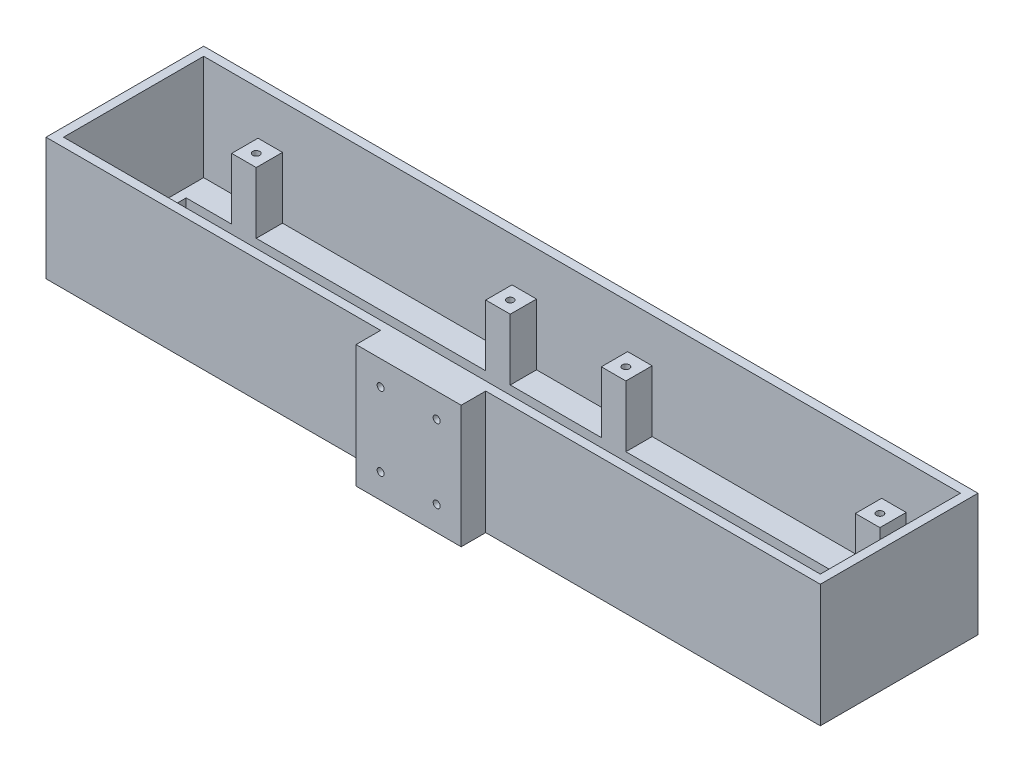
SolidWorks part; units mm, degrees
ref_plane "Front Plane" through (0, 0, 0) normal (0, 0, 1) x (1, 0, 0)
ref_plane "Top Plane" through (0, 0, 0) normal (0, 1, 0) x (1, 0, 0)
ref_plane "Right Plane" through (0, 0, 0) normal (1, 0, 0) x (0, 0, -1)
sketch "Sketch1" plane through (0, 0, 0) normal (0, 1, 0) x (1, 0, 0)
  line L0 (0, 0) -> (0, 46.1847) construction
  line L1 (-110.5, 22.5) -> (110.5, 22.5)
  line L2 (-110.5, 22.5) -> (-110.5, -22.5)
  line L3 (-110.5, -22.5) -> (110.5, -22.5)
  line L4 (110.5, 22.5) -> (110.5, -22.5)
  line L5 (0, 46.1847) -> (0, 0) construction
  line L6 (0, 0) -> (-132.7699, 0) construction
  line L8 (-27.2143, -70.7906) -> (-28.1151, -66.2212) construction
  dimension "D1" = 45
  dimension "D2" = 221
  dimension "D3" = 110.5
  dimension "D4" = 22.5
extrude "Boss-Extrude1" add sketch "Sketch1" along normal blind 5
sketch "Sketch2" plane through (0, 5, 0) normal (0, 1, 0) x (1, 0, 0)
  line L0 (0, 0) -> (0, 63.4853) construction
  line L1 (-105.5, 12.5) -> (105.5, 12.5)
  line L2 (-105.5, 12.5) -> (-105.5, -12.5)
  line L3 (-105.5, -12.5) -> (105.5, -12.5)
  line L4 (105.5, 12.5) -> (105.5, -12.5)
  line L5 (0, 63.4853) -> (0, -74.9421) construction
  line L6 (0, -74.9421) -> (0, 0) construction
  line L7 (0, 0) -> (-181.4639, 0) construction
  line L8 (-181.4639, 0) -> (180.3828, 0) construction
  point P8 (0, -5.7284)
  dimension "D1" = 25
  dimension "D2" = 211
  dimension "D3" = 105.5
  dimension "D4" = 12.5
extrude "Cut-Extrude1" cut sketch "Sketch2" against normal blind 2.5
sketch "Sketch3" plane through (0, 2.5, 0) normal (0, 1, 0) x (1, 0, 0)
  line L0 (0, -84.5319) -> (0, 82.5317) construction
  line L1 (0, 82.5317) -> (0, 0) construction
  line L2 (0, 0) -> (-169.1228, 0) construction
  line L3 (-169.1228, 0) -> (142.1549, 0) construction
  circle A0 centre (-53, 0) radius 8
  circle A1 centre (53, 0) radius 8
  dimension "D1" = 53
  dimension "D2" = 53
extrude "Cut-Extrude2" cut sketch "Sketch3" against normal blind 2.5
sketch "Sketch4" plane through (0, 5, 0) normal (0, 1, 0) x (1, 0, 0)
  line L0 (0, 66.7486) -> (0, -72.9211) construction
  line L1 (0, -72.9211) -> (0, 0) construction
  line L2 (0, 0) -> (-130.6196, 0) construction
  line L3 (-130.6196, 0) -> (143.6753, 0) construction
sketch "Sketch6" plane through (0, 5, 0) normal (0, 1, 0) x (1, 0, 0)
  line L1 (-110.5, -22.5) -> (110.5, -22.5)
  line L3 (110.5, 22.5) -> (-110.5, 22.5)
  line L6 (-110.5, -20) -> (110.5, -20)
  line L10 (0, 66.7486) -> (0, -72.9211) construction
  line L11 (-110.5, -20) -> (-110.5, -22.5)
  line L12 (110.5, -20) -> (110.5, -22.5)
  line L13 (-110.5, 22.5) -> (-110.5, 20)
  line L14 (-110.5, 22.5) -> (-110.5, -22.5) construction
  line L15 (-110.5, 20) -> (110.5, 20)
  line L16 (110.5, -22.5) -> (110.5, 22.5) construction
  line L17 (110.5, 20) -> (110.5, 22.5)
  line L19 (108, 20) -> (110.5, 20)
  line L20 (108, 20) -> (108, -20)
  line L25 (108, -20) -> (110.5, -20)
  line L26 (110.5, 20) -> (110.5, -20)
  line L31 (-110.5, 20) -> (-108, 20)
  line L32 (-110.5, 20) -> (-110.5, -20)
  line L33 (-110.5, -20) -> (-108, -20)
  line L34 (-108, 20) -> (-108, -20)
  line M12 (-110.5, 22.5) -> (-110.5, -22.5)
  line M14 (110.5, -22.5) -> (110.5, 22.5)
  line M15 (110.5, 22.5) -> (-110.5, 22.5)
  dimension "D2" = 2.5
  dimension "D3" = 2.5
  dimension "D4" = 2.5
  dimension "D6" = 2.5
  dimension "D7" = 40
  dimension "D8" = 108
  dimension "D9" = 221
  dimension "D10" = 2.5
extrude "Boss-Extrude3" add sketch "Sketch6" along normal blind 30 contours L34 L15 L6 M12 | L15 M12 M14 M15 | L20 L25 L26 L19
sketch "Sketch7" plane through (0, 5, 0) normal (0, 1, 0) x (1, 0, 0)
  line L0 (105.5, 12.5) -> (-105.5, 12.5) construction
  line L1 (-92.5, 20) -> (-85.5, 20)
  line L2 (-92.5, 20) -> (-92.5, 12.5)
  line L3 (-92.5, 12.5) -> (-85.5, 12.5)
  line L4 (-85.5, 20) -> (-85.5, 12.5)
  line L5 (-105.5, 12.5) -> (-105.5, -12.5) construction
  line L6 (-105.5, -12.5) -> (105.5, -12.5) construction
  line L7 (-92.5, -12.5) -> (-85.5, -12.5)
  line L8 (-92.5, -12.5) -> (-92.5, -20)
  line L9 (-92.5, -20) -> (-85.5, -20)
  line L10 (-85.5, -12.5) -> (-85.5, -20)
  line L11 (-108, -20) -> (108, -20) construction
  line L14 (-108, 20) -> (108, 20) construction
  line L15 (-20, 20) -> (-13, 20)
  line L16 (-20, 20) -> (-20, 12.5)
  line L17 (-20, 12.5) -> (-13, 12.5)
  line L18 (-13, 20) -> (-13, 12.5)
  line L19 (105.5, 12.5) -> (-105.5, 12.5) construction
  line L20 (0, 66.7486) -> (0, -72.9211) construction
  line L21 (-105.5, -12.5) -> (105.5, -12.5) construction
  line L22 (-20, -12.5) -> (-13, -12.5)
  line L23 (-20, -12.5) -> (-20, -20)
  line L24 (-20, -20) -> (-13, -20)
  line L25 (-13, -12.5) -> (-13, -20)
  line L26 (-108, -20) -> (108, -20) construction
  line L27 (13, 20) -> (20, 20)
  line L28 (13, 20) -> (13, 12.5)
  line L29 (13, 12.5) -> (20, 12.5)
  line L30 (20, 20) -> (20, 12.5)
  line L31 (13, -12.5) -> (20, -12.5)
  line L32 (13, -12.5) -> (13, -20)
  line L33 (13, -20) -> (20, -20)
  line L34 (20, -12.5) -> (20, -20)
  line L35 (105.5, -12.5) -> (105.5, 12.5) construction
  line L36 (85.5, 20) -> (92.5, 20)
  line L37 (85.5, 20) -> (85.5, 12.5)
  line L38 (85.5, 12.5) -> (92.5, 12.5)
  line L39 (92.5, 20) -> (92.5, 12.5)
  line L40 (105.5, -12.5) -> (105.5, 12.5) construction
  line L41 (85.5, -12.5) -> (92.5, -12.5)
  line L42 (85.5, -12.5) -> (85.5, -20)
  line L43 (85.5, -20) -> (92.5, -20)
  line L44 (92.5, -12.5) -> (92.5, -20)
  dimension "D1" = 7
  dimension "D2" = 13
  dimension "D3" = 7
  dimension "D4" = 7
  dimension "D5" = 13
  dimension "D6" = 7.5
  dimension "D7" = 7
  dimension "D8" = 13
  dimension "D9" = 13
  dimension "D10" = 13
  dimension "D11" = 7
  dimension "D12" = 7
  dimension "D13" = 13
  dimension "D14" = 7
  dimension "D15" = 13
  dimension "D16" = 7
  dimension "D17" = 13
extrude "Boss-Extrude4" add sketch "Sketch7" along normal blind 17.5
sketch "Sketch9" plane through (0, 22.5, 0) normal (0, 1, 0) x (1, 0, 0)
  line L0 (-85.5, 12.5) -> (-85.5, 20) construction
  line L1 (-92.5, 12.5) -> (-85.5, 12.5) construction
  line L2 (-85.5, -20) -> (-85.5, -12.5) construction
  line L6 (-105.5, -12.5) -> (105.5, -12.5) construction
  line L7 (-20, 12.5) -> (-13, 12.5) construction
  line L8 (-20, 20) -> (-20, 12.5) construction
  line L10 (-20, -12.5) -> (-20, -20) construction
  line L11 (105.5, 12.5) -> (-105.5, 12.5) construction
  line L12 (13, 20) -> (13, 12.5) construction
  line L13 (20, -20) -> (20, -12.5) construction
  line L14 (92.5, 12.5) -> (92.5, 20) construction
  line L15 (85.5, 12.5) -> (92.5, 12.5) construction
  line L16 (92.5, -12.5) -> (85.5, -12.5) construction
  line L18 (85.5, -12.5) -> (85.5, -20) construction
  circle A0 centre (-89, 16) radius 1
  circle A1 centre (-89, -16) radius 1
  circle A2 centre (-16.5, 16) radius 1
  circle A3 centre (-16.5, -16) radius 1
  circle A4 centre (16.5, 16) radius 1
  circle A5 centre (16.5, -16) radius 1
  circle A6 centre (89, 16) radius 1
  circle A7 centre (89, -16) radius 1
  dimension "D3" = 3.5
  dimension "D5" = 3.5
  dimension "D7" = 3.5
  dimension "D9" = 3.5
  dimension "D11" = 3.5
  dimension "D13" = 3.5
  dimension "D15" = 3.5
  dimension "D1" = 3.5
  dimension "D2" = 3.5
  dimension "D4" = 3.5
  dimension "D6" = 3.5
  dimension "D8" = 3.5
  dimension "D10" = 3.5
  dimension "D12" = 3.5
  dimension "D14" = 3.5
  dimension "D16" = 3.5
extrude "Cut-Extrude3" cut sketch "Sketch9" against normal blind 6
sketch "Sketch10" plane through (0, 0, 22.5) normal (0, 0, 1) x (1, 0, 0)
  line L0 (-110.5, 35) -> (110.5, 35) construction
  line L1 (-15, 35) -> (15, 35)
  line L2 (-15, 35) -> (-15, 0)
  line L3 (-15, 0) -> (15, 0)
  line L4 (15, 35) -> (15, 0)
  line L5 (-110.5, 0) -> (110.5, 0) construction
  line L6 (110.5, 35) -> (110.5, 0) construction
  dimension "D1" = 95.5
  dimension "D2" = 30
extrude "Boss-Extrude5" add sketch "Sketch10" along normal blind 7
sketch "Sketch11" plane through (0, 0, 29.5) normal (0, 0, 1) x (1, 0, 0)
  line L0 (-15, 35) -> (-15, 0) construction
  line L1 (15, 35) -> (-15, 35) construction
  line L2 (15, 0) -> (15, 35) construction
  line L3 (-15, 35) -> (-15, 0) construction
  line L4 (-15, 0) -> (15, 0) construction
  circle A0 centre (-8, 28) radius 1
  circle A1 centre (8, 28) radius 1
  circle A2 centre (-8, 7) radius 1
  circle A3 centre (8, 7) radius 1
  dimension "D1" = 7
  dimension "D2" = 7
  dimension "D3" = 7
  dimension "D4" = 7
  dimension "D5" = 7
  dimension "D6" = 7
  dimension "D7" = 7
  dimension "D8" = 7
extrude "Cut-Extrude4" cut sketch "Sketch11" against normal blind 6
